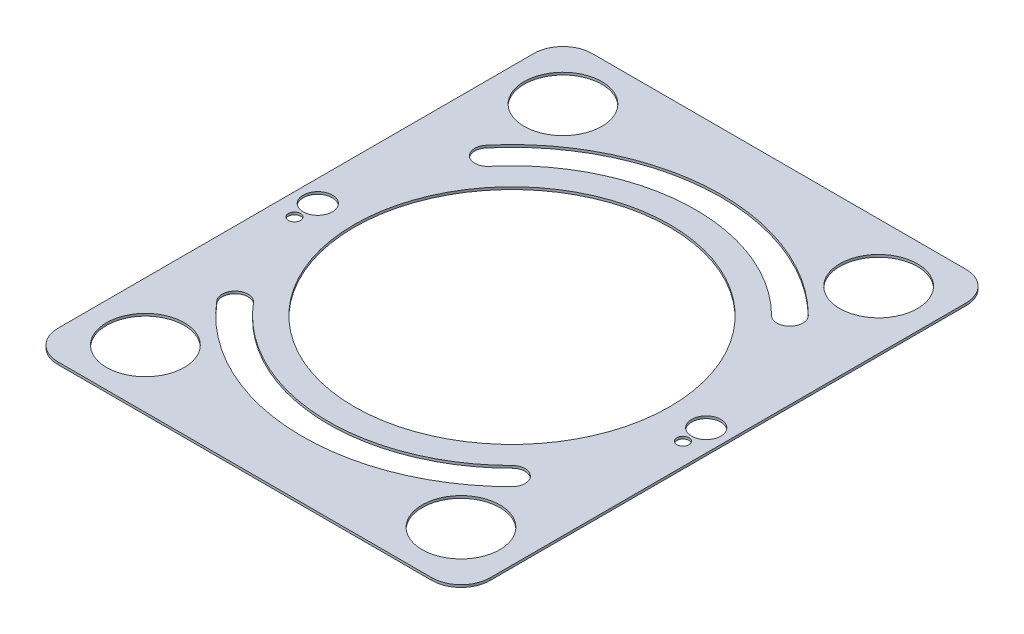
SolidWorks part; units mm, degrees
ref_plane "Front Plane" through (0, 0, 0) normal (0, 0, 1) x (1, 0, 0)
ref_plane "Top Plane" through (0, 0, 0) normal (0, 1, 0) x (1, 0, 0)
ref_plane "Right Plane" through (0, 0, 0) normal (1, 0, 0) x (0, 0, -1)
sketch "Sketch1" plane through (0, 0, 0) normal (0, 1, 0) x (1, 0, 0)
  line L0 (0, 0) -> (-52.4741, 44.031) construction
  line L1 (-61.1187, 87.3125) -> (61.1187, 87.3125)
  line L2 (-70.6438, 77.7875) -> (-70.6438, -77.7875)
  line L3 (-61.1187, -87.3125) -> (61.1187, -87.3125)
  line L4 (70.6437, 77.7875) -> (70.6437, -77.7875)
  line L5 (-70.6438, 87.3125) -> (70.6437, -87.3125) construction
  line L6 (-70.6438, -87.3125) -> (70.6437, 87.3125) construction
  line L7 (-51.5938, 68.2625) -> (51.5937, 68.2625) construction
  line L8 (-51.5938, 68.2625) -> (-51.5938, -68.2625) construction
  line L9 (-51.5938, -68.2625) -> (51.5937, -68.2625) construction
  line L10 (51.5937, 68.2625) -> (51.5937, -68.2625) construction
  line L11 (-51.5938, 68.2625) -> (51.5937, -68.2625) construction
  line L12 (-51.5938, -68.2625) -> (51.5937, 68.2625) construction
  line L13 (0, 0) -> (48.4368, 48.4368) construction
  line L14 (0, 0) -> (0, 87.3125) construction
  line L15 (-70.6438, 0) -> (70.6437, 0) construction
  arc A0 (-70.6438, -77.7875) -> (-61.1187, -87.3125) centre (-61.1188, -77.7875) ccw
  arc A1 (61.1187, -87.3125) -> (70.6437, -77.7875) centre (61.1187, -77.7875) ccw
  arc A2 (61.1187, 87.3125) -> (70.6437, 77.7875) centre (61.1187, 77.7875) cw
  arc A3 (-61.1187, 87.3125) -> (-70.6438, 77.7875) centre (-61.1188, 77.7875) ccw
  circle A4 centre (-51.5938, 68.2625) radius 12.7
  circle A5 centre (51.5937, 68.2625) radius 12.7
  circle A6 centre (-51.5938, -68.2625) radius 12.7
  circle A7 centre (51.5937, -68.2625) radius 12.7
  arc A10 (-52.4741, 44.031) -> (-45.9627, 38.5673) centre (-49.2184, 41.2991) ccw
  arc A11 (42.4264, 42.4264) -> (-45.9627, 38.5673) centre (0, 0) ccw
  arc A12 (48.4368, 48.4368) -> (-52.4741, 44.031) centre (0, 0) ccw
  arc A13 (42.4264, 42.4264) -> (48.4368, 48.4368) centre (45.4316, 45.4316) ccw
  arc A14 (42.4264, -42.4264) -> (-45.9627, -38.5673) centre (0, 0) cw
  arc A15 (-52.4741, -44.031) -> (-45.9627, -38.5673) centre (-49.2184, -41.2991) cw
  arc A16 (48.4368, -48.4368) -> (-52.4741, -44.031) centre (0, 0) cw
  arc A17 (42.4264, -42.4264) -> (48.4368, -48.4368) centre (45.4316, -45.4316) cw
  circle A18 centre (0, 0) radius 51.5938
  circle A19 centre (-63.5, 0) radius 4.7625
  circle A20 centre (63.5, 0) radius 4.7625
  circle A21 centre (-63.5, -7.62) radius 1.9844
  circle A22 centre (63.5, -7.62) radius 1.9844
  point P0 (0, 0)
  point P18 (0, 0)
  dimension "D3" = 9.525
  dimension "D6" = 25.4
  dimension "D7" = 60
  dimension "D8" = 8.5
  dimension "D11" = 103.1875
  dimension "D12" = 9.525
  dimension "D14" = 7.1437
  dimension "D15" = 7.62
  dimension "D16" = 3.9688
  dimension "D17" = 7.62
  dimension "D18" = 3.9688
  dimension "D1" = 141.2875
  dimension "D2" = 174.625
  dimension "D4" = 103.1875
  dimension "D5" = 136.525
  dimension "D9" = 45
  dimension "D10" = 95
  dimension "D13" = 7.1437
extrude "Boss-Extrude1" add sketch "Sketch1" along normal blind 0.7937
